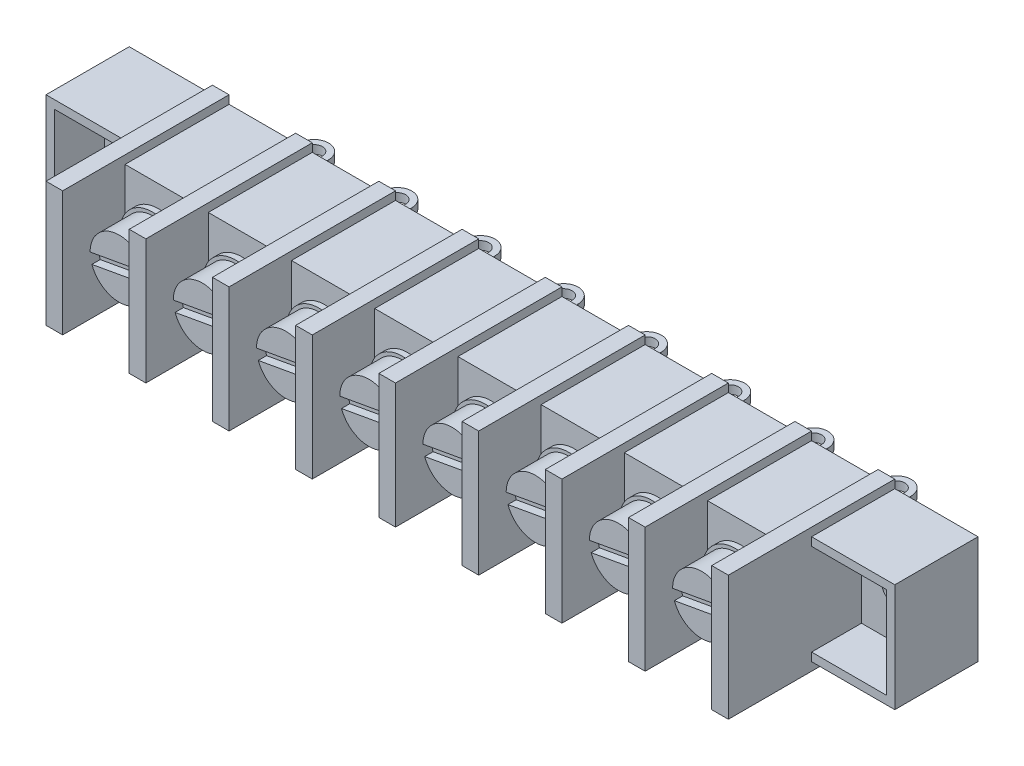
SolidWorks part; units mm, degrees
ref_plane "Спереди" through (0, 0, 0) normal (0, 0, 1) x (1, 0, 0)
ref_plane "Сверху" through (0, 0, 0) normal (0, 1, 0) x (1, 0, 0)
ref_plane "Справа" through (0, 0, 0) normal (1, 0, 0) x (0, 0, -1)
sketch "Эскиз1" plane through (0, 0, 0) normal (0, 0, 1) x (1, 0, 0)
  line L0 (-47.9787, 0) -> (44.4324, 0) construction
  line L1 (0, 0) -> (0, 38.9044) construction
  line L2 (-41, -7.5) -> (41, -7.5)
  line L3 (-41, -7.5) -> (-41, 7.5)
  line L4 (-41, 7.5) -> (41, 7.5)
  line L5 (41, -7.5) -> (41, 7.5)
  dimension "D1" = 15
  dimension "D2" = 82
extrude "Вытянуть1" add sketch "Эскиз1" along normal blind 10
sketch "Эскиз2" plane through (0, 0, 10) normal (0, 0, 1) x (1, 0, 0)
  line L0 (41, 7.5) -> (-41, 7.5) construction
  line L1 (-41, -7.5) -> (-39, -7.5)
  line L2 (-41, -7.5) -> (-41, 7.5)
  line L3 (-41, 7.5) -> (-39, 7.5)
  line L4 (-39, -7.5) -> (-39, 7.5)
  line L5 (0, 13.212) -> (0, -10.8914) construction
  line L6 (-41, -7.5) -> (41, -7.5) construction
  line L7 (-31, -7.5) -> (-29, -7.5)
  line L8 (-31, -7.5) -> (-31, 7.5)
  line L9 (-31, 7.5) -> (-29, 7.5)
  line L10 (-29, -7.5) -> (-29, 7.5)
  line L11 (-30, 8.3866) -> (-30, -8.2377) construction
  line L12 (1, 7.5) -> (-1, 7.5)
  line L13 (1, -7.5) -> (1, 7.5)
  line L14 (1, -7.5) -> (-1, -7.5)
  line L15 (-1, -7.5) -> (-1, 7.5)
  line L16 (29, -7.5) -> (29, 7.5)
  line L17 (31, 7.5) -> (29, 7.5)
  line L18 (31, -7.5) -> (31, 7.5)
  line L19 (31, -7.5) -> (29, -7.5)
  line L20 (39, -7.5) -> (39, 7.5)
  line L21 (41, 7.5) -> (39, 7.5)
  line L22 (41, -7.5) -> (41, 7.5)
  line L23 (41, -7.5) -> (39, -7.5)
  line L24 (-21, -7.5) -> (-19, -7.5)
  line L25 (-21, -7.5) -> (-21, 7.5)
  line L26 (-21, 7.5) -> (-19, 7.5)
  line L27 (-19, -7.5) -> (-19, 7.5)
  line L28 (9, -7.5) -> (9, 7.5)
  line L29 (-11, -7.5) -> (-9, -7.5)
  line L30 (-11, -7.5) -> (-11, 7.5)
  line L31 (-11, 7.5) -> (-9, 7.5)
  line L32 (-9, -7.5) -> (-9, 7.5)
  line L33 (11, 7.5) -> (9, 7.5)
  line L34 (-10, 8.3866) -> (-10, -8.2377) construction
  line L35 (-20, 8.3866) -> (-20, -8.2377) construction
  line L36 (11, -7.5) -> (11, 7.5)
  line L37 (11, -7.5) -> (9, -7.5)
  line L38 (19, -7.5) -> (19, 7.5)
  line L39 (21, 7.5) -> (19, 7.5)
  line L40 (21, -7.5) -> (21, 7.5)
  line L41 (21, -7.5) -> (19, -7.5)
  dimension "D1" = 2
  dimension "D2" = 10
  dimension "D3" = 2
  dimension "D4" = 8
extrude "Вытянуть2" add sketch "Эскиз2" along normal blind 10
sketch "Эскиз3" plane through (0, 0, 10) normal (0, 0, 1) x (1, 0, 0)
  line L0 (-35, 10.8914) -> (-35, -9.6255) construction
  line L3 (-31, 7.5) -> (-31, -7.5) construction
  line L4 (-39, -7.5) -> (-39, 7.5) construction
  line L5 (-39, -7.5) -> (-31, -7.5) construction
  line L6 (-39, -7.5) -> (-31, -7.5)
  line L7 (-39, -7.5) -> (-39, 7.5)
  line L8 (-39, 7.5) -> (-31, 7.5)
  line L9 (-31, -7.5) -> (-31, 7.5)
  line L10 (-31, 7.5) -> (-39, 7.5) construction
  line L13 (-21, -7.5) -> (-21, 7.5)
  line L14 (-21, 7.5) -> (-29, 7.5)
  line L15 (-29, 7.5) -> (-29, -7.5)
  line L16 (-29, -7.5) -> (-21, -7.5)
  line L17 (-21, -7.5) -> (-21, 7.5)
  line L18 (-21, 7.5) -> (-29, 7.5)
  line L19 (-29, 7.5) -> (-29, -7.5)
  line L20 (-29, -7.5) -> (-21, -7.5)
  line L21 (-11, -7.5) -> (-11, 7.5)
  line L22 (-11, 7.5) -> (-19, 7.5)
  line L23 (-19, 7.5) -> (-19, -7.5)
  line L24 (-19, -7.5) -> (-11, -7.5)
  line L25 (-11, -7.5) -> (-11, 7.5)
  line L26 (-11, 7.5) -> (-19, 7.5)
  line L27 (-19, 7.5) -> (-19, -7.5)
  line L28 (-19, -7.5) -> (-11, -7.5)
  line L29 (-9, 7.5) -> (-9, -7.5)
  line L30 (-9, -7.5) -> (-1, -7.5)
  line L31 (-1, -7.5) -> (-1, 7.5)
  line L32 (-1, 7.5) -> (-9, 7.5)
  line L33 (-9, 7.5) -> (-9, -7.5)
  line L34 (-9, -7.5) -> (-1, -7.5)
  line L35 (-1, -7.5) -> (-1, 7.5)
  line L36 (-1, 7.5) -> (-9, 7.5)
  line L37 (9, -7.5) -> (9, 7.5)
  line L39 (9, 7.5) -> (1, 7.5)
  line L40 (1, 7.5) -> (1, -7.5)
  line L41 (1, -7.5) -> (9, -7.5)
  line L42 (9, -7.5) -> (9, 7.5)
  line L43 (9, 7.5) -> (1, 7.5)
  line L44 (1, 7.5) -> (1, -7.5)
  line L45 (1, -7.5) -> (9, -7.5)
  line L46 (19, -7.5) -> (19, 7.5)
  line L47 (19, 7.5) -> (11, 7.5)
  line L48 (11, 7.5) -> (11, -7.5)
  line L49 (11, -7.5) -> (19, -7.5)
  line L50 (19, -7.5) -> (19, 7.5)
  line L51 (19, 7.5) -> (11, 7.5)
  line L52 (11, 7.5) -> (11, -7.5)
  line L53 (11, -7.5) -> (19, -7.5)
  line L54 (21, 7.5) -> (21, -7.5)
  line L55 (21, -7.5) -> (29, -7.5)
  line L56 (29, -7.5) -> (29, 7.5)
  line L57 (29, 7.5) -> (21, 7.5)
  line L58 (21, 7.5) -> (21, -7.5)
  line L59 (21, -7.5) -> (29, -7.5)
  line L60 (29, -7.5) -> (29, 7.5)
  line L61 (29, 7.5) -> (21, 7.5)
  line L62 (39, -7.5) -> (39, 7.5)
  line L63 (39, 7.5) -> (31, 7.5)
  line L64 (31, 7.5) -> (31, -7.5)
  line L65 (31, -7.5) -> (39, -7.5)
  line L66 (39, -7.5) -> (39, 7.5)
  line L67 (39, 7.5) -> (31, 7.5)
  line L68 (31, 7.5) -> (31, -7.5)
  line L69 (31, -7.5) -> (39, -7.5)
  dimension "D1" = 8
  dimension "D2" = 0
  dimension "D3" = 0
  dimension "D4" = 0
  dimension "D5" = 0
  dimension "D6" = 0
  dimension "D7" = 0
  dimension "D8" = 0
extrude "Вытянуть3" add sketch "Эскиз3" along normal blind 2.5
sketch "Эскиз4" plane through (0, 0, 12.5) normal (0, 0, 1) x (1, 0, 0)
  line L0 (-24.2616, 0) -> (23.4177, 0) construction
  line L1 (-35, 0) -> (-35, 16.4068) construction
  line L4 (0, 0) -> (0, 14.617) construction
  line L6 (-39, -7.5) -> (-39, 7.5) construction
  line L7 (-31, -7.5) -> (-31, 7.5) construction
  circle A0 centre (-35, 0) radius 3.9
  circle A1 centre (-25, 0) radius 3.9
  circle A2 centre (-15, 0) radius 3.9
  circle A3 centre (-5, 0) radius 3.9
  circle A4 centre (5, 0) radius 3.9
  circle A5 centre (15, 0) radius 3.9
  circle A6 centre (25, 0) radius 3.9
  circle A7 centre (35, 0) radius 3.9
  dimension "D1" = 7.8
  dimension "D2" = 10
extrude "Вытянуть4" add sketch "Эскиз4" along normal blind 0.7
sketch "Эскиз6" plane through (0, 0, 13.2) normal (0, 0, 1) x (1, 0, 0)
  line L0 (0, 0) -> (0, 15.7615) construction
  circle A0 centre (-35, 0) radius 3.5
  circle A1 centre (-35, 0) radius 3.9 construction
  circle A2 centre (-25, 0) radius 3.5
  circle A3 centre (-15, 0) radius 3.5
  circle A4 centre (-5, 0) radius 3.5
  circle A5 centre (5, 0) radius 3.5
  circle A6 centre (15, 0) radius 3.5
  circle A7 centre (25, 0) radius 3.5
  circle A8 centre (35, 0) radius 3.5
  circle A11 centre (5, 0) radius 3.5 [skipped]
  circle A12 centre (15, 0) radius 3.5 [skipped]
  circle A13 centre (25, 0) radius 3.5 [skipped]
  circle A14 centre (35, 0) radius 3.5 [skipped]
  dimension "D1" = 7
  dimension "D2" = 10
extrude "Вытянуть5" add sketch "Эскиз6" along normal blind 4
sketch "Эскиз7" plane through (0, 0, 17.2) normal (0, 0, 1) x (1, 0, 0)
  line L0 (-35, 0) -> (-19.4589, -11.6177) construction
  line L1 (-35, 0) -> (-12.9483, 3.9455) construction
  line L2 (-31.7114, 1.1979) -> (-38.5, -0.0167)
  line L3 (-31.5, 0.0167) -> (-38.2886, -1.1979)
  line L4 (-21.7114, 1.1979) -> (-28.5, -0.0167)
  line L5 (-21.5, 0.0167) -> (-28.2886, -1.1979)
  line L6 (-11.7114, 1.1979) -> (-18.5, -0.0167)
  line L7 (-11.5, 0.0167) -> (-18.2886, -1.1979)
  line L8 (-1.7114, 1.1979) -> (-8.5, -0.0167)
  line L9 (-1.5, 0.0167) -> (-8.2886, -1.1979)
  line L10 (0, 0) -> (0, 13.7349) construction
  line L11 (8.2886, 1.1979) -> (1.5, -0.0167)
  line L12 (8.5, 0.0167) -> (1.7114, -1.1979)
  line L13 (18.2886, 1.1979) -> (11.5, -0.0167)
  line L14 (18.5, 0.0167) -> (11.7114, -1.1979)
  line L15 (28.2886, 1.1979) -> (21.5, -0.0167)
  line L16 (28.5, 0.0167) -> (21.7114, -1.1979)
  line L17 (38.2886, 1.1979) -> (31.5, -0.0167)
  line L18 (38.5, 0.0167) -> (31.7114, -1.1979)
  circle A0 centre (-35, 0) radius 3.5 construction
  arc A1 (-31.5, 0.0167) -> (-31.7114, 1.1979) centre (-35, 0) ccw
  arc A2 (-38.5, -0.0167) -> (-38.2886, -1.1979) centre (-35, 0) ccw
  arc A3 (-21.5, 0.0167) -> (-21.7114, 1.1979) centre (-25, 0) ccw
  arc A4 (-28.5, -0.0167) -> (-28.2886, -1.1979) centre (-25, 0) ccw
  arc A5 (-11.5, 0.0167) -> (-11.7114, 1.1979) centre (-15, 0) ccw
  arc A6 (-18.5, -0.0167) -> (-18.2886, -1.1979) centre (-15, 0) ccw
  arc A7 (-1.5, 0.0167) -> (-1.7114, 1.1979) centre (-5, 0) ccw
  arc A8 (-8.5, -0.0167) -> (-8.2886, -1.1979) centre (-5, 0) ccw
  arc A9 (8.5, 0.0167) -> (8.2886, 1.1979) centre (5, 0) ccw
  arc A10 (1.5, -0.0167) -> (1.7114, -1.1979) centre (5, 0) ccw
  arc A11 (18.5, 0.0167) -> (18.2886, 1.1979) centre (15, 0) ccw
  arc A12 (11.5, -0.0167) -> (11.7114, -1.1979) centre (15, 0) ccw
  arc A13 (28.5, 0.0167) -> (28.2886, 1.1979) centre (25, 0) ccw
  arc A14 (21.5, -0.0167) -> (21.7114, -1.1979) centre (25, 0) ccw
  arc A15 (38.5, 0.0167) -> (38.2886, 1.1979) centre (35, 0) ccw
  arc A16 (31.5, -0.0167) -> (31.7114, -1.1979) centre (35, 0) ccw
  dimension "D2" = 1.2
extrude "Вырез-Вытянуть1" cut sketch "Эскиз7" against normal blind 1
sketch "Эскиз8" plane through (0, 0, 0) normal (0, 0, -1) x (-1, 0, 0)
  line L0 (-23.7342, 0) -> (23.7342, 0) construction
  line L1 (0, 12.8956) -> (0, -12.4209) construction
  line L2 (23.25, -0.5) -> (26.75, -0.5)
  line L3 (23.25, -0.5) -> (23.25, 0.5)
  line L4 (23.25, 0.5) -> (26.75, 0.5)
  line L5 (26.75, -0.5) -> (26.75, 0.5)
  line L6 (13.25, -0.5) -> (16.75, -0.5)
  line L7 (13.25, -0.5) -> (13.25, 0.5)
  line L8 (13.25, 0.5) -> (16.75, 0.5)
  line L9 (16.75, -0.5) -> (16.75, 0.5)
  line L10 (3.25, -0.5) -> (6.75, -0.5)
  line L11 (3.25, -0.5) -> (3.25, 0.5)
  line L12 (3.25, 0.5) -> (6.75, 0.5)
  line L13 (6.75, -0.5) -> (6.75, 0.5)
  line L14 (-6.75, -0.5) -> (-3.25, -0.5)
  line L15 (-6.75, -0.5) -> (-6.75, 0.5)
  line L16 (-6.75, 0.5) -> (-3.25, 0.5)
  line L17 (-3.25, -0.5) -> (-3.25, 0.5)
  line L18 (-16.75, -0.5) -> (-13.25, -0.5)
  line L19 (-16.75, -0.5) -> (-16.75, 0.5)
  line L20 (-16.75, 0.5) -> (-13.25, 0.5)
  line L21 (-13.25, -0.5) -> (-13.25, 0.5)
  line L22 (-26.75, -0.5) -> (-23.25, -0.5)
  line L23 (-26.75, -0.5) -> (-26.75, 0.5)
  line L24 (-26.75, 0.5) -> (-23.25, 0.5)
  line L25 (-23.25, -0.5) -> (-23.25, 0.5)
  line L26 (-36.75, -0.5) -> (-33.25, -0.5)
  line L27 (-36.75, -0.5) -> (-36.75, 0.5)
  line L28 (-36.75, 0.5) -> (-33.25, 0.5)
  line L29 (-33.25, -0.5) -> (-33.25, 0.5)
  line L47 (33.25, -0.5) -> (36.75, -0.5)
  line L48 (33.25, -0.5) -> (33.25, 0.5)
  line L49 (33.25, 0.5) -> (36.75, 0.5)
  line L50 (36.75, -0.5) -> (36.75, 0.5)
extrude "Вытянуть6" add sketch "Эскиз8" along normal blind 8
sketch "Эскиз10" plane through (-41, 0, 0) normal (-1, 0, 0) x (0, 0, 1)
  line L0 (10, -7.5) -> (10, 7.5)
  line L4 (0, 7.5) -> (0, -7.5)
  line L5 (0, -7.5) -> (20, -7.5)
  line L6 (20, -7.5) -> (20, 7.5)
  line L7 (20, 7.5) -> (0, 7.5)
  line L8 (0, 7.5) -> (0, -7.5)
  line L9 (0, -7.5) -> (10, -7.5)
  line L11 (10, 7.5) -> (0, 7.5)
  dimension "D2" = 10
  dimension "D1" = 0
extrude "Вытянуть7" add sketch "Эскиз10" along normal blind 10
sketch "Эскиз11" plane through (41, 0, 0) normal (1, 0, 0) x (0, 0, -1)
  line L4 (0, 7.5) -> (-10, 7.5)
  line L5 (0, -7.5) -> (0, 7.5)
  line L6 (-10, -7.5) -> (0, -7.5)
  line L7 (-10, 7.5) -> (-10, -7.5)
  line L8 (0, 7.5) -> (-10, 7.5)
  line L9 (0, -7.5) -> (0, 7.5)
  line L10 (-10, -7.5) -> (0, -7.5)
  line L11 (-10, 7.5) -> (-10, -7.5)
  dimension "D1" = 0
extrude "Вытянуть8" add sketch "Эскиз11" along normal blind 10
sketch "Эскиз12" plane through (0, 0, 10) normal (0, 0, 1) x (1, 0, 0)
  line L0 (-54.3833, 0) -> (55.0396, 0) construction
  line L1 (0, 0) -> (0, 16.7838) construction
  circle A0 centre (45, 0) radius 1.6
  circle A1 centre (-45, 0) radius 1.6
  dimension "D1" = 3.2
  dimension "D2" = 45
extrude "Вырез-Вытянуть2" cut sketch "Эскиз12" against normal blind 10
sketch "Эскиз13" plane through (0, 0, 10) normal (0, 0, 1) x (1, 0, 0)
  line L0 (41, 7.5) -> (41, -7.5) construction
  line L1 (41, -5.5) -> (50, -5.5)
  line L2 (41, -5.5) -> (41, 5.5)
  line L3 (41, 5.5) -> (50, 5.5)
  line L4 (50, -5.5) -> (50, 5.5)
  line L5 (51, 7.5) -> (51, -7.5) construction
  line L6 (51, 7.5) -> (41, 7.5) construction
  line L7 (51, -7.5) -> (41, -7.5) construction
  line L8 (0, 0) -> (0, 15.322) construction
  line L9 (-50, -5.5) -> (-50, 5.5)
  line L10 (-41, 5.5) -> (-50, 5.5)
  line L11 (-41, -5.5) -> (-41, 5.5)
  line L12 (-41, -5.5) -> (-50, -5.5)
  dimension "D1" = 1
  dimension "D2" = 2
  dimension "D3" = 2
extrude "Вырез-Вытянуть3" cut sketch "Эскиз13" against normal blind 6
sketch "Эскиз14" plane through (0, 0, 12.5) normal (0, 0, 1) x (1, 0, 0)
  line L0 (0, 0) -> (64.3223, 0) construction
  line L1 (0, 0) -> (0, 17.1529) construction
  line L2 (39, 7.5) -> (39, -7.5) construction
  line L3 (31, 7.5) -> (39, 7.5)
  line L4 (31, 7.5) -> (31, 6.5)
  line L5 (31, 6.5) -> (39, 6.5)
  line L6 (39, 7.5) -> (39, 6.5)
  line L7 (41, 7.5) -> (41, 5.5) construction
  line L8 (41, 6.5) -> (51, 6.5)
  line L9 (41, 6.5) -> (41, 7.5)
  line L10 (41, 7.5) -> (51, 7.5)
  line L11 (51, 6.5) -> (51, 7.5)
  line L12 (51, -6.5) -> (51, -7.5)
  line L13 (41, -7.5) -> (51, -7.5)
  line L14 (41, -6.5) -> (41, -7.5)
  line L15 (41, -6.5) -> (51, -6.5)
  line L16 (39, -7.5) -> (39, -6.5)
  line L17 (31, -6.5) -> (39, -6.5)
  line L18 (31, -7.5) -> (31, -6.5)
  line L19 (31, -7.5) -> (39, -7.5)
  line L20 (21, 7.5) -> (29, 7.5)
  line L21 (21, 7.5) -> (21, 6.5)
  line L22 (21, 6.5) -> (29, 6.5)
  line L23 (29, 7.5) -> (29, 6.5)
  line L24 (29, -7.5) -> (29, -6.5)
  line L25 (21, -6.5) -> (29, -6.5)
  line L26 (21, -7.5) -> (21, -6.5)
  line L27 (21, -7.5) -> (29, -7.5)
  line L28 (11, 7.5) -> (19, 7.5)
  line L29 (11, 7.5) -> (11, 6.5)
  line L30 (11, 6.5) -> (19, 6.5)
  line L31 (19, 7.5) -> (19, 6.5)
  line L32 (19, -7.5) -> (19, -6.5)
  line L33 (11, -6.5) -> (19, -6.5)
  line L34 (11, -7.5) -> (11, -6.5)
  line L35 (11, -7.5) -> (19, -7.5)
  line L36 (1, 7.5) -> (9, 7.5)
  line L37 (1, 7.5) -> (1, 6.5)
  line L38 (1, 6.5) -> (9, 6.5)
  line L39 (9, 7.5) -> (9, 6.5)
  line L40 (9, -7.5) -> (9, -6.5)
  line L41 (1, -6.5) -> (9, -6.5)
  line L42 (1, -7.5) -> (1, -6.5)
  line L43 (1, -7.5) -> (9, -7.5)
  line L44 (-9, 7.5) -> (-1, 7.5)
  line L45 (-9, 7.5) -> (-9, 6.5)
  line L46 (-9, 6.5) -> (-1, 6.5)
  line L47 (-1, 7.5) -> (-1, 6.5)
  line L48 (-1, -7.5) -> (-1, -6.5)
  line L49 (-9, -6.5) -> (-1, -6.5)
  line L50 (-9, -7.5) -> (-9, -6.5)
  line L51 (-9, -7.5) -> (-1, -7.5)
  line L52 (-19, 7.5) -> (-11, 7.5)
  line L53 (-19, 7.5) -> (-19, 6.5)
  line L54 (-19, 6.5) -> (-11, 6.5)
  line L55 (-11, 7.5) -> (-11, 6.5)
  line L56 (-11, -7.5) -> (-11, -6.5)
  line L57 (-19, -6.5) -> (-11, -6.5)
  line L58 (-19, -7.5) -> (-19, -6.5)
  line L59 (-19, -7.5) -> (-11, -7.5)
  line L60 (-29, 7.5) -> (-21, 7.5)
  line L61 (-29, 7.5) -> (-29, 6.5)
  line L62 (-29, 6.5) -> (-21, 6.5)
  line L63 (-21, 7.5) -> (-21, 6.5)
  line L64 (-21, -7.5) -> (-21, -6.5)
  line L65 (-29, -6.5) -> (-21, -6.5)
  line L66 (-29, -7.5) -> (-29, -6.5)
  line L67 (-29, -7.5) -> (-21, -7.5)
  line L68 (-39, 7.5) -> (-31, 7.5)
  line L69 (-39, 7.5) -> (-39, 6.5)
  line L70 (-39, 6.5) -> (-31, 6.5)
  line L71 (-31, 7.5) -> (-31, 6.5)
  line L72 (-31, -7.5) -> (-31, -6.5)
  line L73 (-39, -6.5) -> (-31, -6.5)
  line L74 (-39, -7.5) -> (-39, -6.5)
  line L75 (-39, -7.5) -> (-31, -7.5)
  line L76 (-41, -6.5) -> (-51, -6.5)
  line L77 (-41, -6.5) -> (-41, -7.5)
  line L78 (-41, -7.5) -> (-51, -7.5)
  line L79 (-51, -6.5) -> (-51, -7.5)
  line L80 (-51, 6.5) -> (-51, 7.5)
  line L81 (-41, 7.5) -> (-51, 7.5)
  line L82 (-41, 6.5) -> (-41, 7.5)
  line L83 (-41, 6.5) -> (-51, 6.5)
  dimension "D1" = 1
extrude "Вырез-Вытянуть4" cut sketch "Эскиз14" against normal blind 20
sketch "Эскиз15" plane through (0, -0.5, 0) normal (0, -1, 0) x (1, 0, 0)
  line L0 (33.25, -6.2124) -> (33.25, -10.5448)
  line L3 (33.25, -8) -> (33.25, 0) construction
  line L4 (33.25, -10.5448) -> (36.75, -10.5448)
  line L5 (34, -6.2124) -> (34, -5.8124)
  line L6 (36, -6.2124) -> (36, -5.8124)
  line L7 (36.75, -6.2124) -> (36.75, -10.5448)
  line L8 (36.75, -8) -> (36.75, 0) construction
  arc A0 (34, -6.2124) -> (36, -6.2124) centre (35, -6.2124) ccw
  arc A1 (34, -5.8124) -> (36, -5.8124) centre (35, -5.8124) cw
  arc A2 (33.25, -6.2124) -> (36.75, -6.2124) centre (35, -6.2124) ccw
  dimension "D1" = 2
extrude "Вырез-Вытянуть5" cut sketch "Эскиз15" against normal blind 20
pattern_linear "Линейный массив1" count 8 spacing 10 along (-1, 0, 0) of "Вырез-Вытянуть5"
